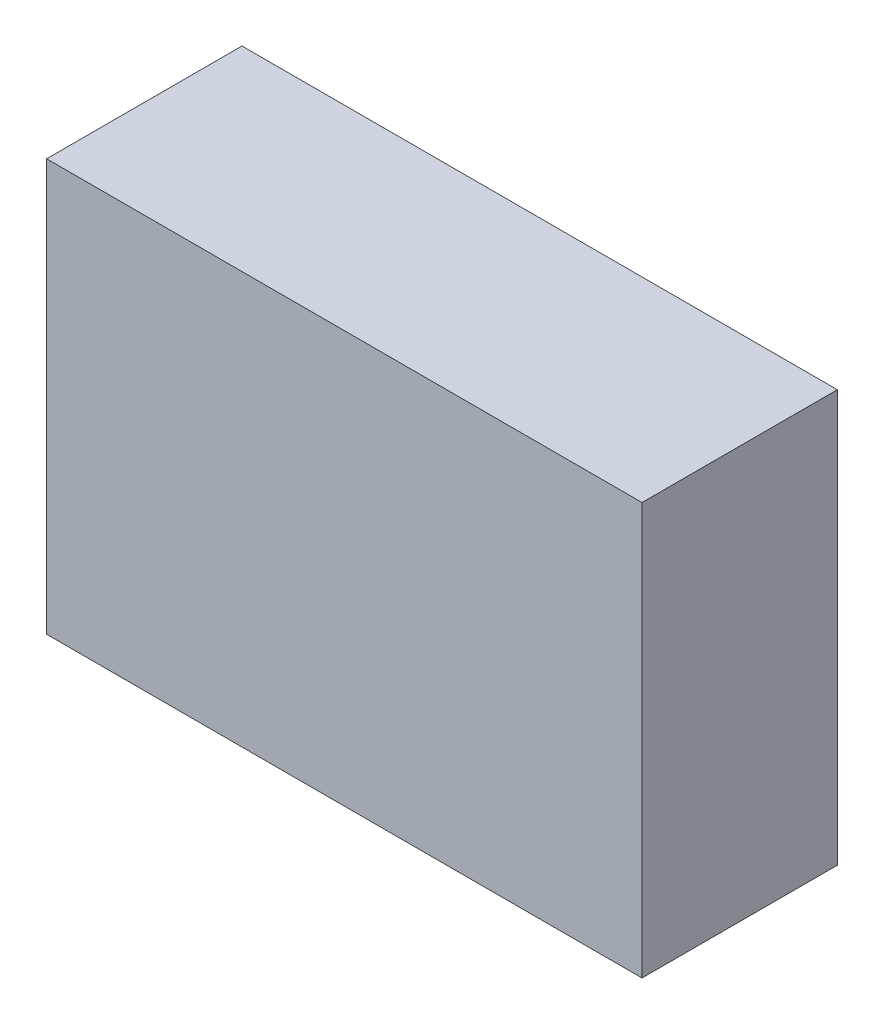
SolidWorks part; units mm, degrees
ref_plane "Front Plane" through (0, 0, 0) normal (0, 0, 1) x (1, 0, 0)
ref_plane "Top Plane" through (0, 0, 0) normal (0, 1, 0) x (1, 0, 0)
ref_plane "Right Plane" through (0, 0, 0) normal (1, 0, 0) x (0, 0, -1)
sketch "Sketch1" plane through (0, 0, 0) normal (0, 0, 1) x (1, 0, 0)
  line L0 (-1.524, 1.016) -> (1.524, 1.016)
  line L1 (1.524, 1.016) -> (1.524, -1.0922)
  line L2 (1.524, -1.0922) -> (-1.524, -1.0922)
  line L3 (-1.524, -1.0922) -> (-1.524, 1.016)
extrude "Component_Outline" add sketch "Sketch1" along normal blind 1 separate body
sketch3d "3DSketch1"
  line L0 (0, 0, 0) -> (1, 0, 0)
  line L1 (0, 0, 0) -> (0, 1, 0)
  line L2 (0, 0, 0) -> (0, 0, 1)
  point P0 (0, 0, 0)
